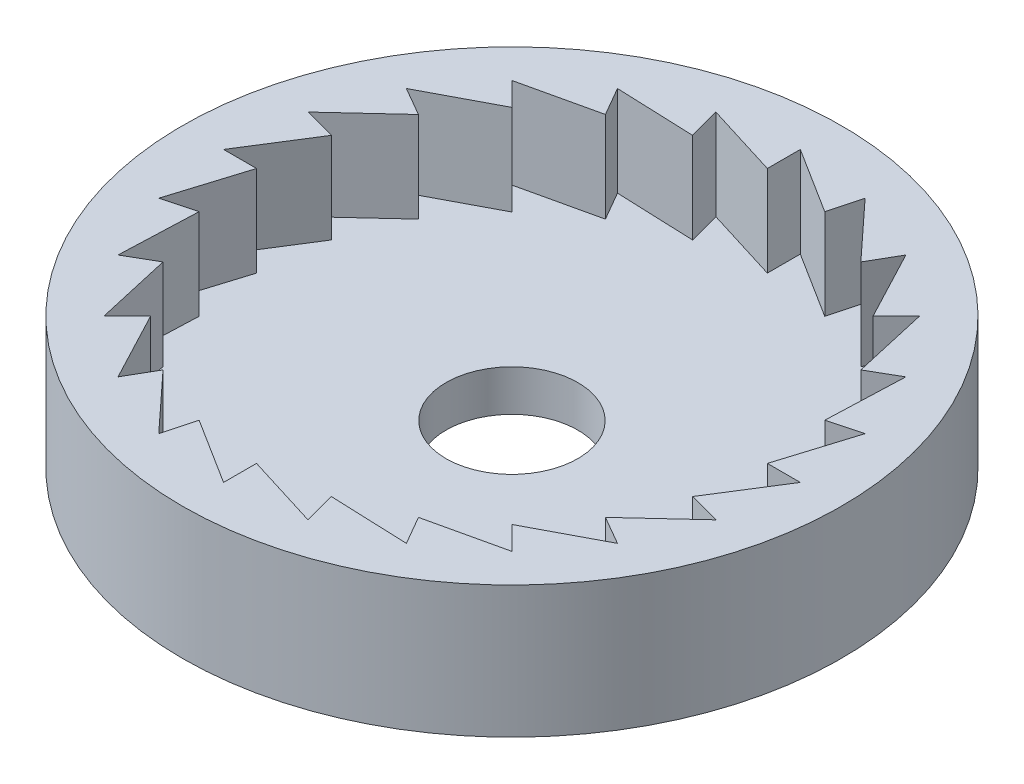
SolidWorks part; units mm, degrees
ref_plane "Front Plane" through (0, 0, 0) normal (0, 0, 1) x (1, 0, 0)
ref_plane "Top Plane" through (0, 0, 0) normal (0, 1, 0) x (1, 0, 0)
ref_plane "Right Plane" through (0, 0, 0) normal (1, 0, 0) x (0, 0, -1)
sketch "Sketch1" plane through (0, 0, 0) normal (0, 1, 0) x (1, 0, 0)
  line L0 (0, 0) -> (0, 20) construction
  line L1 (-8.4609, 18.1222) -> (0, 15.5) construction
  line L2 (0, 0) -> (-5.1764, 19.3185) construction
  line L3 (0, 15.5) -> (0, 17.5) construction
  line L4 (-3.4823, 19.6945) -> (4.0117, 14.9719) construction
  line L5 (4.0117, 14.9719) -> (4.5293, 16.9037) construction
  line L6 (1.7337, 19.9247) -> (7.75, 13.4234) construction
  line L7 (7.75, 13.4234) -> (8.75, 15.1554) construction
  line L8 (6.8315, 18.7971) -> (10.9602, 10.9602) construction
  line L9 (10.9602, 10.9602) -> (12.3744, 12.3744) construction
  line L10 (11.4638, 16.3885) -> (13.4234, 7.75) construction
  line L11 (13.4234, 7.75) -> (15.1554, 8.75) construction
  line L12 (15.3148, 12.863) -> (14.9719, 4.0117) construction
  line L13 (14.9719, 4.0117) -> (16.9037, 4.5293) construction
  line L14 (18.1222, 8.4609) -> (15.5, 0) construction
  line L15 (15.5, 0) -> (17.5, 0) construction
  line L16 (19.6945, 3.4823) -> (14.9719, -4.0117) construction
  line L17 (14.9719, -4.0117) -> (16.9037, -4.5293) construction
  line L18 (19.9247, -1.7337) -> (13.4234, -7.75) construction
  line L19 (13.4234, -7.75) -> (15.1554, -8.75) construction
  line L20 (18.7971, -6.8315) -> (10.9602, -10.9602) construction
  line L21 (10.9602, -10.9602) -> (12.3744, -12.3744) construction
  line L22 (16.3885, -11.4638) -> (7.75, -13.4234) construction
  line L23 (7.75, -13.4234) -> (8.75, -15.1554) construction
  line L24 (12.863, -15.3148) -> (4.0117, -14.9719) construction
  line L25 (4.0117, -14.9719) -> (4.5293, -16.9037) construction
  line L26 (8.4609, -18.1222) -> (0, -15.5) construction
  line L27 (0, -15.5) -> (0, -17.5) construction
  line L28 (3.4823, -19.6945) -> (-4.0117, -14.9719) construction
  line L29 (-4.0117, -14.9719) -> (-4.5293, -16.9037) construction
  line L30 (-1.7337, -19.9247) -> (-7.75, -13.4234) construction
  line L31 (-7.75, -13.4234) -> (-8.75, -15.1554) construction
  line L32 (-6.8315, -18.7971) -> (-10.9602, -10.9602) construction
  line L33 (-10.9602, -10.9602) -> (-12.3744, -12.3744) construction
  line L34 (-11.4638, -16.3885) -> (-13.4234, -7.75) construction
  line L35 (-13.4234, -7.75) -> (-15.1554, -8.75) construction
  line L36 (-15.3148, -12.863) -> (-14.9719, -4.0117) construction
  line L37 (-14.9719, -4.0117) -> (-16.9037, -4.5293) construction
  line L38 (-18.1222, -8.4609) -> (-15.5, 0) construction
  line L39 (-15.5, 0) -> (-17.5, 0) construction
  line L40 (-19.6945, -3.4823) -> (-14.9719, 4.0117) construction
  line L41 (-14.9719, 4.0117) -> (-16.9037, 4.5293) construction
  line L42 (0, 0) -> (0, 15.5) construction
  line L43 (-19.9247, 1.7337) -> (-13.4234, 7.75) construction
  line L44 (-13.4234, 7.75) -> (-15.1554, 8.75) construction
  line L45 (-18.7971, 6.8315) -> (-10.9602, 10.9602) construction
  line L46 (-10.9602, 10.9602) -> (-12.3744, 12.3744) construction
  line L47 (-16.3885, 11.4638) -> (-7.75, 13.4234) construction
  line L48 (-7.75, 13.4234) -> (-8.75, 15.1554) construction
  line L49 (-12.863, 15.3148) -> (-4.0117, 14.9719) construction
  line L50 (-4.0117, 14.9719) -> (-4.5293, 16.9037) construction
  circle A0 centre (0, 0) radius 20
  circle A1 centre (0, 0) radius 17.5
  point P9 (-4.5293, 16.9037)
  dimension "D1" = 40
  dimension "D4" = 35
  dimension "D3" = 2
  dimension "D5" = 15
  dimension "D2" = 2.5
  dimension "D6" = 24
extrude "Boss-Extrude2" add sketch "Sketch1" along normal blind 8 contours A1 | A0 A1
shell "Shell2" thickness 2.5
sketch "Sketch3" plane through (0, 2.5, 0) normal (0, 1, 0) x (1, 0, 0)
  line L0 (-8.4609, 18.1222) -> (0, 15.5) construction
  line L1 (-8.4609, 18.1222) -> (0, 15.5)
  line L2 (0, 15.5) -> (0, 17.5)
  line L3 (-3.4823, 19.6945) -> (4.0117, 14.9719)
  line L4 (4.0117, 14.9719) -> (4.5293, 16.9037)
  line L5 (1.7337, 19.9247) -> (7.75, 13.4234)
  line L6 (7.75, 13.4234) -> (8.75, 15.1554)
  line L7 (6.8315, 18.7971) -> (10.9602, 10.9602)
  line L8 (10.9602, 10.9602) -> (12.3744, 12.3744)
  line L9 (11.4638, 16.3885) -> (13.4234, 7.75)
  line L10 (13.4234, 7.75) -> (15.1554, 8.75)
  line L11 (15.3148, 12.863) -> (14.9719, 4.0117)
  line L12 (14.9719, 4.0117) -> (16.9037, 4.5293)
  line L13 (18.1222, 8.4609) -> (15.5, 0)
  line L14 (15.5, 0) -> (17.5, 0)
  line L15 (19.6945, 3.4823) -> (14.9719, -4.0117)
  line L16 (14.9719, -4.0117) -> (16.9037, -4.5293)
  line L17 (19.9247, -1.7337) -> (13.4234, -7.75)
  line L18 (13.4234, -7.75) -> (15.1554, -8.75)
  line L19 (18.7971, -6.8315) -> (10.9602, -10.9602)
  line L20 (10.9602, -10.9602) -> (12.3744, -12.3744)
  line L21 (16.3885, -11.4638) -> (7.75, -13.4234)
  line L22 (7.75, -13.4234) -> (8.75, -15.1554)
  line L23 (12.863, -15.3148) -> (4.0117, -14.9719)
  line L24 (4.0117, -14.9719) -> (4.5293, -16.9037)
  line L25 (8.4609, -18.1222) -> (0, -15.5)
  line L26 (0, -15.5) -> (0, -17.5)
  line L27 (3.4823, -19.6945) -> (-4.0117, -14.9719)
  line L28 (-4.0117, -14.9719) -> (-4.5293, -16.9037)
  line L29 (-1.7337, -19.9247) -> (-7.75, -13.4234)
  line L30 (-7.75, -13.4234) -> (-8.75, -15.1554)
  line L31 (-6.8315, -18.7971) -> (-10.9602, -10.9602)
  line L32 (-10.9602, -10.9602) -> (-12.3744, -12.3744)
  line L33 (-11.4638, -16.3885) -> (-13.4234, -7.75)
  line L34 (-13.4234, -7.75) -> (-15.1554, -8.75)
  line L35 (-15.3148, -12.863) -> (-14.9719, -4.0117)
  line L36 (-14.9719, -4.0117) -> (-16.9037, -4.5293)
  line L37 (-18.1222, -8.4609) -> (-15.5, 0)
  line L38 (-15.5, 0) -> (-17.5, 0)
  line L39 (-19.6945, -3.4823) -> (-14.9719, 4.0117)
  line L40 (-14.9719, 4.0117) -> (-16.9037, 4.5293)
  line L41 (0, 0) -> (0, 15.5) construction
  line L42 (-19.9247, 1.7337) -> (-13.4234, 7.75)
  line L43 (-13.4234, 7.75) -> (-15.1554, 8.75)
  line L44 (-18.7971, 6.8315) -> (-10.9602, 10.9602)
  line L45 (-10.9602, 10.9602) -> (-12.3744, 12.3744)
  line L46 (-16.3885, 11.4638) -> (-7.75, 13.4234)
  line L47 (-7.75, 13.4234) -> (-8.75, 15.1554)
  line L48 (-12.863, 15.3148) -> (-4.0117, 14.9719)
  line L49 (-4.0117, 14.9719) -> (-4.5293, 16.9037)
  circle A0 centre (0, 0) radius 17.5 construction
  circle A1 centre (0, 0) radius 17.5 construction
  circle A2 centre (0, 0) radius 17.5
  circle M2 centre (0, 0) radius 17.5
  dimension "D1" = 24
extrude "Boss-Extrude3" add sketch "Sketch3" along normal up to surface (5.5 mm away) contours L35 L36 M2 | L37 L38 M2 | L39 L40 M2 | L1 L2 M2 | L3 L4 M2 | L5 L6 M2 | L7 L8 M2 | L9 L10 M2 | L11 L12 M2 | L13 L14 M2 | L15 L16 M2 | L17 L18 M2 | L19 L20 M2 | L21 L22 M2 | L23 L24 M2 | L25 L26 M2 | L27 L28 M2 | L29 L30 M2 | L31 L32 M2 | L33 L34 M2 | L42 L43 M2 | L44 L45 M2 | L46 L47 M2 | L48 L49 M2 up to face at (0, 8, 17.5)
sketch "Sketch4" plane through (0, 2.5, 0) normal (0, 1, 0) x (1, 0, 0)
  circle A0 centre (0, 0) radius 4
  dimension "D1" = 8
extrude "Cut-Extrude1" cut sketch "Sketch4" against normal blind 12
equation "\"D5@Sketch1\"=360/\"D6@Sketch1\""
